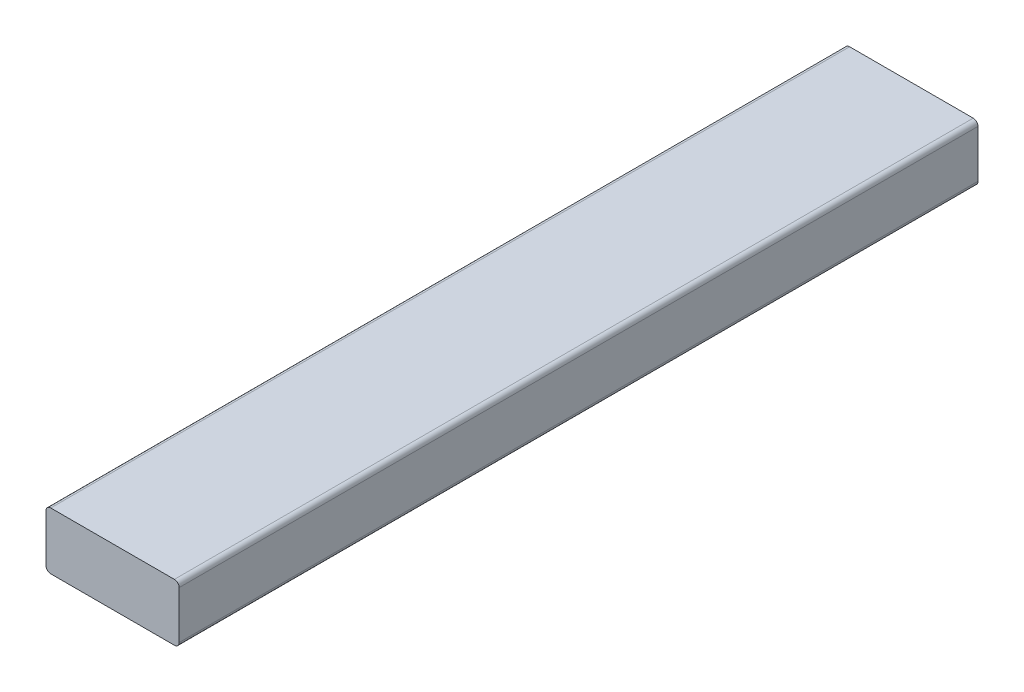
SolidWorks part; units mm, degrees
ref_plane "Front Plane" through (0, 0, 0) normal (0, 0, 1) x (1, 0, 0)
ref_plane "Top Plane" through (0, 0, 0) normal (0, 1, 0) x (1, 0, 0)
ref_plane "Right Plane" through (0, 0, 0) normal (1, 0, 0) x (0, 0, -1)
sketch "Sketch1" plane through (0, 0, 0) normal (0, 0, 1) x (1, 0, 0)
  line L1 (-44.45, -19.05) -> (44.45, -19.05)
  line L2 (-44.45, -19.05) -> (-44.45, 19.05)
  line L3 (-44.45, 19.05) -> (44.45, 19.05)
  line L4 (44.45, -19.05) -> (44.45, 19.05)
  line L5 (-44.45, -19.05) -> (44.45, 19.05) construction
  line L6 (-44.45, 19.05) -> (44.45, -19.05) construction
  point P0 (0, 0)
  dimension "D1" = 38.1
  dimension "D2" = 88.9
extrude "Boss-Extrude1" add sketch "Sketch1" along normal blind 533.4
fillet "Fillet1" radius 3.175 4 edges at (-44.45, -19.05, 266.7) (-44.45, 19.05, 266.7) (44.45, -19.05, 266.7) (44.45, 19.05, 266.7)
